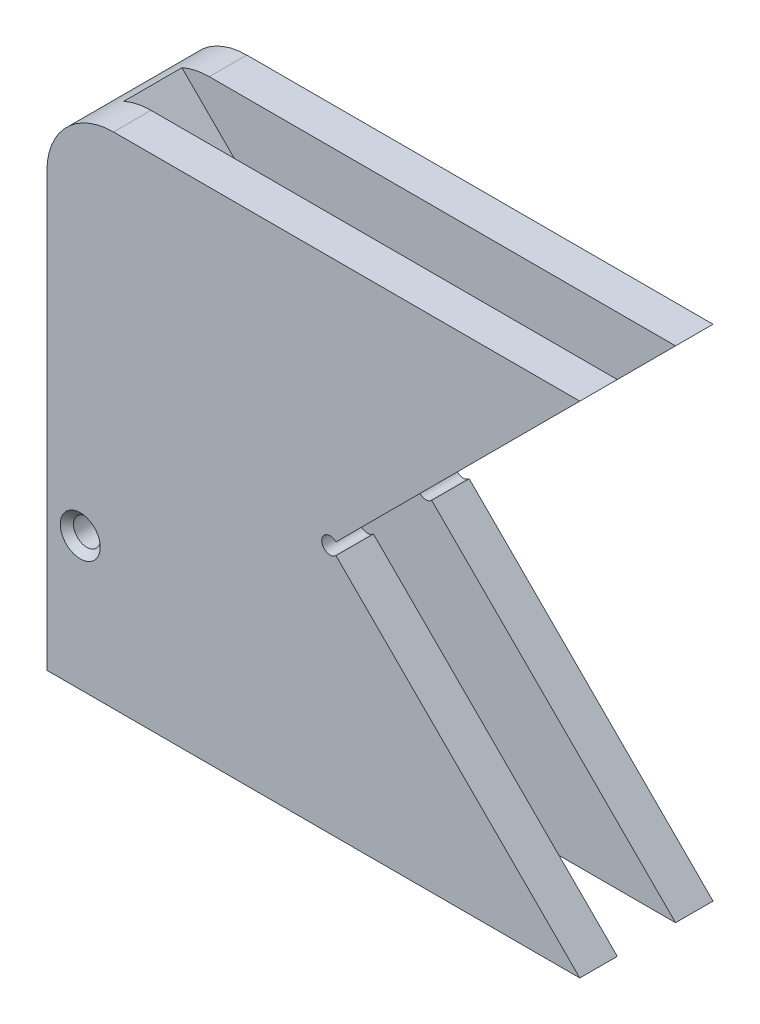
SolidWorks part; units mm, degrees
material "Plain Carbon Steel"
ref_plane "Front" through (0, 0, 0) normal (0, 0, 1) x (1, 0, 0)
ref_plane "Top" through (0, 0, 0) normal (0, 1, 0) x (1, 0, 0)
ref_plane "Right" through (0, 0, 0) normal (1, 0, 0) x (0, 0, -1)
sketch "Sketch2" plane through (0, 0, 0) normal (0, 0, 1) x (1, 0, 0)
  line L0 (0, 0) -> (0, 95.25)
  line L1 (0, 95.25) -> (101.6, 95.25)
  line L2 (101.6, 95.25) -> (53.975, 47.625)
  line L3 (53.975, 47.625) -> (101.6, 0)
  line L4 (101.6, 0) -> (0, 0)
  dimension "D1" = 95.25
  dimension "D2" = 101.6
  dimension "D3" = 45
  dimension "D4" = 47.625
extrude "Boss-Extrude1" add sketch "Sketch2" along normal mid plane 25.4
hole_wizard "1/8 (0.125) Diameter Hole1" positions "Sketch4" profile "Sketch3" hole size "1/8" standard "ANSI Inch" end condition through all
sketch "Sketch4" plane through (0, 0, 12.7) normal (0, 0, 1) x (1, 0, 0)
  point P0 (53.975, 47.625)
sketch "Sketch3" plane through (53.975, 47.625, 12.7) normal (1, 0, 0) x (0, -1, 0)
  line L0 (0, 0) -> (0, 25.4)
  line L1 (0, 25.4) -> (1.5875, 25.4)
  line L2 (1.5875, 25.4) -> (1.5875, 0)
  line L5 (1.5875, 0) -> (0, 0)
  line L11 (0, -6.35) -> (0, 107.95) construction
  dimension "Thru Hole Dia." = 3.175
  dimension "Thru Hole Depth" = 25.4
fillet "Fillet1" radius 12.7 1 edges at (0, 95.25, 0)
hole_wizard "1/4-20 Tapped Hole1" positions "Sketch6" profile "Sketch5" tap size "1/4-20" standard "ANSI Inch" end condition through all
sketch "Sketch6" plane through (0, 0, 12.7) normal (0, 0, 1) x (1, 0, 0)
  line L0 (0, 0) -> (101.6, 0) construction
  line L1 (0, 82.55) -> (0, 0) construction
  point P0 (6.35, 25.4)
  dimension "D1" = 25.4
  dimension "D2" = 6.35
cosmetic thread "Hole Thread1" parameters "D2"=6.35
sketch "Sketch5" plane through (6.35, 25.4, 12.7) normal (1, 0, 0) x (0, -1, 0)
  line L0 (0, 0) -> (0, 25.4)
  line L1 (0, 25.4) -> (3.81, 25.4)
  line L2 (2.5527, 24.1427) -> (2.5527, 1.2573)
  line L3 (2.5527, 1.2573) -> (3.81, 0)
  line L5 (3.81, 0) -> (0, 0)
  line L6 (-2.5527, 1.2573) -> (-3.81, 0) construction
  line L7 (3.81, 25.4) -> (2.5527, 24.1427)
  line L8 (-3.81, 25.4) -> (-2.5527, 24.1427) construction
  line L11 (0, -6.35) -> (0, 107.95) construction
  dimension "Thru Tap Drill Dia." = 5.1054
  dimension "Thru Tap Drill Depth" = 25.4
  dimension "Near C'Sink Dia." = 7.62
  dimension "Near C'Sink Angle" = 90
  dimension "Far C'Sink Dia." = 7.62
  dimension "Far C'Sink Angle" = 90
hole_wizard "1/4-20 Tapped Hole2" positions "Sketch8" profile "Sketch7" tap size "1/4-20" standard "ANSI Inch"
sketch "Sketch8" plane through (0, 0, 0) normal (-1, 0, 0) x (0, 0, 1)
  point P0 (0, 41.275)
  point P2 (0, 9.525)
  dimension "D1" = 9.525
  dimension "D2" = 31.75
sketch "Sketch7" plane through (0, 41.275, 0) normal (0, 1, 0) x (0, 0, 1)
  line L0 (0, 0) -> (0, 17.4088)
  line L1 (0, 17.4088) -> (2.5527, 15.875)
  line L2 (2.5527, 15.875) -> (2.5527, 1.2573)
  line L3 (2.5527, 1.2573) -> (3.81, 0)
  line L5 (3.81, 0) -> (0, 0)
  line L6 (-2.5527, 1.2573) -> (-3.81, 0) construction
  line L10 (0, 17.4088) -> (-2.5527, 15.875) construction
  line L11 (0, -6.35) -> (0, 107.95) construction
  dimension "Tap Drill Dia." = 5.1054
  dimension "Tap Drill Depth" = 15.875
  dimension "Near C'Sink Dia." = 7.62
  dimension "Near C'Sink Angle" = 90
  dimension "Drill Angle" = 118
cosmetic thread "Hole Thread2" parameters "D1"=12.7, "D2"=6.35
cosmetic thread "Hole Thread3" parameters "D1"=12.7, "D2"=6.35
sketch "Sketch9" plane through (0, 0, 0) normal (0, 0, 1) x (1, 0, 0)
  line L0 (101.6, 95.25) -> (12.7, 95.25) construction
  line L1 (55.0975, 48.7475) -> (101.6, 95.25) construction
  line L2 (101.6, 0) -> (55.0975, 46.5025) construction
  line L3 (0, 0) -> (101.6, 0) construction
  line L4 (101.6, 95.25) -> (6.35, 95.25)
  line L5 (6.35, 0) -> (101.6, 95.25)
  line L6 (101.6, 0) -> (6.35, 95.25)
  line L7 (6.35, 0) -> (101.6, 0)
extrude "Cut-Extrude1" cut sketch "Sketch9" against normal mid plane 11.1125 contours L6 L5 L4 | L5 L7 L6
